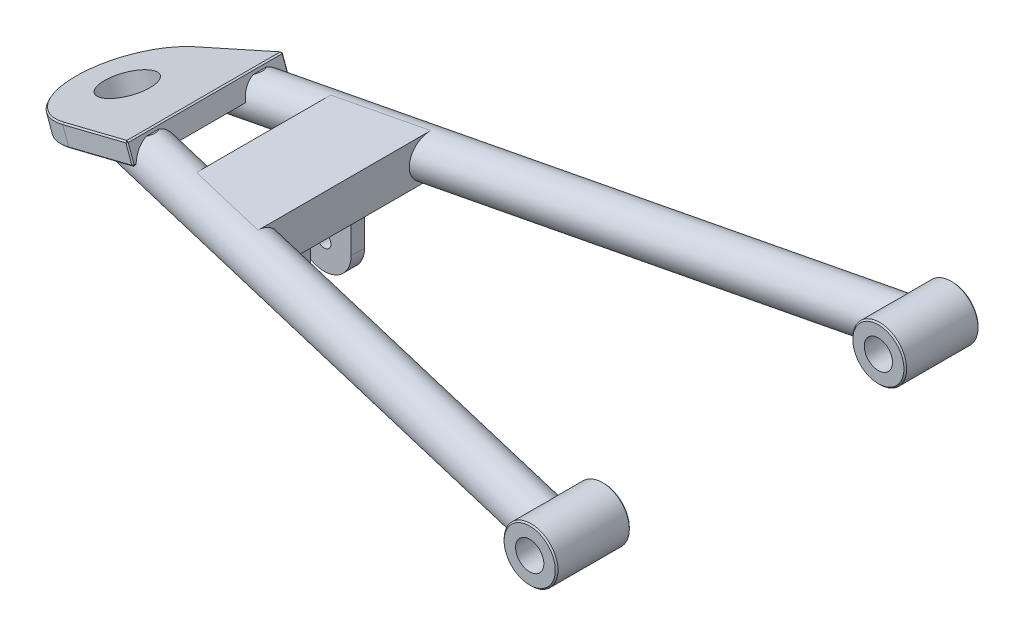
SolidWorks part; units mm, degrees
ref_plane "Front Plane" through (0, 0, 0) normal (0, 0, 1) x (1, 0, 0)
ref_plane "Top Plane" through (0, 0, 0) normal (0, 1, 0) x (1, 0, 0)
ref_plane "Right Plane" through (0, 0, 0) normal (1, 0, 0) x (0, 0, -1)
sketch "Sketch1" plane through (0, 0, 0) normal (0, 1, 0) x (1, 0, 0)
  line L0 (0, -178.98) -> (0, 178.98) construction
  line L1 (10.5, 101.98) -> (10.5, 169.3673) construction
  line L2 (0, 156.98) -> (-9.5, 156.98)
  line L3 (0, 156.98) -> (0, 101.98)
  line L4 (0, 101.98) -> (-9.5, 101.98)
  line L5 (-9.5, 156.98) -> (-9.5, 101.98)
  line L6 (0, 0) -> (-427.43, 0) construction
  line L11 (10.5, -101.98) -> (10.5, -169.3673) construction
  line L12 (0, -101.98) -> (-9.5, -101.98)
  line L13 (-9.5, -156.98) -> (-9.5, -101.98)
  line L14 (0, -156.98) -> (-9.5, -156.98)
  line L15 (0, -156.98) -> (0, -101.98)
  line L16 (-9.5, 129.48) -> (-427.43, 30) construction
  line L17 (-9.5, -129.48) -> (-427.43, -30) construction
  point P3 (0, 0)
  dimension "D1" = 357.96
  dimension "D2" = 22
  dimension "D3" = 9.5
  dimension "D4" = 55
  dimension "D5" = 20
  dimension "D6" = 427.43
  dimension "D7" = 30
revolve "Revolve1" add sketch "Sketch1" angle 360 about L1
ref_plane "Plane1" through (-427.43, 0, -30) normal (-0.9728, 0, 0.2316) x (0.2316, 0, 0.9728)
sketch "Sketch2" plane through (-427.43, 0, -30) normal (-0.9728, 0, 0.2316) x (0.2316, 0, 0.9728)
  circle A0 centre (0, 0) radius 15.5
  circle A1 centre (0, 0) radius 12.65
  dimension "D1" = 31
  dimension "D2" = 25.3
extrude "Boss-Extrude1" add sketch "Sketch2" along direction (-0.9728, 0, 0.2316) on the side against the normal up to surface (425.917 mm away)
ref_plane "Plane2" through (0, 0, 0) normal (0, 0, -1) x (-1, 0, 0)
ref_plane "Plane3" through (-427.43, 0, 30) normal (-0.9728, 0, -0.2316) x (-0.2316, 0, 0.9728)
sketch "Sketch3" plane through (-427.43, 0, 30) normal (-0.9728, 0, -0.2316) x (-0.2316, 0, 0.9728)
  circle A0 centre (0, 0) radius 15.5
  circle A1 centre (0, 0) radius 12.65
  dimension "D1" = 31
  dimension "D2" = 25.3
extrude "Boss-Extrude2" add sketch "Sketch3" along direction (-0.9728, 0, -0.2316) on the side against the normal up to surface (433.296 mm away)
sketch "Sketch22" plane through (-397.753, 0, -94.6773) normal (-0.9728, 0, -0.2316) x (-0.2316, 0, 0.9728)
  circle A0 centre (128.1606, 0) radius 12.65 construction
  circle A1 centre (128.1606, 0) radius 12.65 construction
  point P8 (128.1606, -12.65)
sketch "Sketch24" plane through (-397.753, 0, 94.6773) normal (-0.9728, 0, 0.2316) x (0.2316, 0, 0.9728)
  circle A0 centre (-128.1606, 0) radius 12.65
  circle A1 centre (-128.1606, 0) radius 12.65 construction
  point P5 (-128.1606, -12.65)
ref_plane "Plane4" through (-45.9342, 126.2031, 0) normal (-0.342, 0.9397, 0) x (0, 0, -1)
sketch "Sketch8" plane through (-45.9342, 126.2031, 0) normal (-0.342, 0.9397, 0) x (0, 0, -1)
  line L0 (-30, 401.6528) -> (30, 401.6528) construction
  line L1 (0, 401.6528) -> (0, 453.9985) construction
  line L2 (-58.1255, 358.3228) -> (58.1255, 358.3228)
  line L3 (0, 0) -> (0, 401.6528) construction
  line L4 (-58.1255, 358.3228) -> (-49.4901, 418.3228)
  line L5 (58.1255, 358.3228) -> (49.4901, 418.3228)
  circle A0 centre (0, 419.6528) radius 18
  arc A1 (-49.4901, 418.3228) -> (49.4901, 418.3228) centre (0, 411.2) cw
  point P11 (0, 358.3228)
  dimension "D1" = 36
  dimension "D5" = 50
  dimension "D2" = 81.81
  dimension "D3" = 60
  dimension "D4" = 61.33
ref_plane "Plane5" through (-377.4302, -137.3734, 0) normal (-0.9397, -0.342, 0) x (0, 0, 1)
sketch "Sketch9" plane through (-377.4302, -137.3734, 0) normal (-0.9397, -0.342, 0) x (0, 0, 1)
  line L1 (100, 146.1897) -> (-100, 146.1897)
  line L2 (100, 146.1897) -> (100, 179.4241)
  line L3 (100, 179.4241) -> (-100, 179.4241)
  line L4 (-100, 146.1897) -> (-100, 179.4241)
  point P5 (0, 146.1897)
  dimension "D1" = 200
  dimension "D2" = 33.2344
extrude "Cut-Extrude2" cut sketch "Sketch9" against normal mid plane 397
extrude "Boss-Extrude3" add sketch "Sketch8" along normal blind 15
chamfer "Chamfer1" distance 1 angle 45 4 edges at (30.5, 0, -156.98) (30.5, 0, -101.98) (30.5, 0, 101.98) (30.5, 0, 156.98)
chamfer "Chamfer2" distance 1 angle 45 11 edges at (-385.2126, 10.6972, 58.1255) (-385.2126, 10.6972, -58.1255) (-387.7778, 17.7449, 0) (-415.9686, 7.4843, 53.8078) (-415.9686, 7.4843, -53.8078) (-484.4507, -17.4412, 0) (-382.6475, 3.6495, 57.1351) (-410.8383, -6.6111, 53.8078) (-410.8383, -6.6111, -53.8078) (-479.3204, -31.5366, 0) (-382.6475, 3.6495, -57.1351)
sketch "Sketch13" plane through (0, 0, 0) normal (0, 0, 1) x (1, 0, 0)
  line L0 (0, 0) -> (-457.43, 0) construction
  line L1 (-427.43, -15.5) -> (-2.1392, -15.5) construction
  line L2 (-344.1087, 15.5) -> (-284.1087, 15.5)
  line L3 (-344.1087, 15.5) -> (-344.1087, -15.5)
  line L4 (-344.1087, -15.5) -> (-284.1087, -15.5)
  line L5 (-284.1087, 15.5) -> (-284.1087, -15.5)
  line L6 (-344.1087, 15.5) -> (-284.1087, -15.5) construction
  line L7 (-344.1087, -15.5) -> (-284.1087, 15.5) construction
  point P4 (-314.1087, 0)
  dimension "D1" = 60
  dimension "D2" = 170
extrude "Boss-Extrude5" add sketch "Sketch13" along normal up to surface and the other way up to surface up to face at (-397.3162, 2.0937, 39.0511) other way up to face at (-397.3162, 2.0937, -39.0511)
ref_plane "Plane6" through (0, 0, 15) normal (0, 0, 1) x (1, 0, 0)
chamfer "Chamfer4" distance 1 angle 45 2 edges at (-427.1286, -15.4452, -28.7336) (-427.1286, -15.4452, 28.7336)
sketch "Sketch18" plane through (0, 0, 0) normal (0, 0, 1) x (1, 0, 0)
  line L0 (-334.1087, -15.5) -> (-294.1087, -15.5)
  line L1 (-284.1087, -15.5) -> (-344.1087, -15.5) construction
  line L2 (-334.1087, -15.5) -> (-334.1087, -45.5)
  line L3 (-294.1087, -15.5) -> (-294.1087, -45.5)
  line L4 (-284.1087, -15.5) -> (-344.1087, -15.5) construction
  arc A0 (-334.1087, -45.5) -> (-294.1087, -45.5) centre (-314.1087, -45.5) ccw
  circle A1 centre (-314.1087, -45.5) radius 5
  point P5 (-314.1087, -15.5)
  dimension "D1" = 10
  dimension "D2" = 30
  dimension "D3" = 40
sketch "Sketch19" plane through (0, 0, 15) normal (0, 0, 1) x (1, 0, 0)
  line L0 (-334.1087, -15.5) -> (-334.1087, -45.5) construction
  line L1 (-294.1087, -15.5) -> (-294.1087, -45.5) construction
  line L2 (-334.1087, -15.5) -> (-294.1087, -15.5) construction
  line L3 (-334.1087, -15.5) -> (-334.1087, -45.5)
  line L4 (-294.1087, -15.5) -> (-294.1087, -45.5)
  line L5 (-334.1087, -15.5) -> (-294.1087, -15.5)
  circle A0 centre (-314.1087, -45.5) radius 5 construction
  arc A1 (-334.1087, -45.5) -> (-294.1087, -45.5) centre (-314.1087, -45.5) ccw construction
  circle A2 centre (-314.1087, -45.5) radius 5
  arc A3 (-334.1087, -45.5) -> (-294.1087, -45.5) centre (-314.1087, -45.5) ccw
extrude "Boss-Extrude7" add sketch "Sketch19" along normal blind 10
mirror "Mirror2" about plane through (0, 0, 0) normal (0, 0, 1) of "Boss-Extrude7"
ref_plane "Plane7" through (-48.4993, 133.2508, 0) normal (0.342, -0.9397, 0) x (-0.9397, -0.342, 0)
equation "\"Inner diameter tube\" = 25.3mm "
equation "\"D2@Sketch2\"=\"Inner diameter tube\""
equation "\"D2@Sketch3\"=\"Inner diameter tube\""
equation "\"BoltNominalDiameter\" = 10mm "
equation "\"BushingInnerDiameter\" = 10.1mm "
